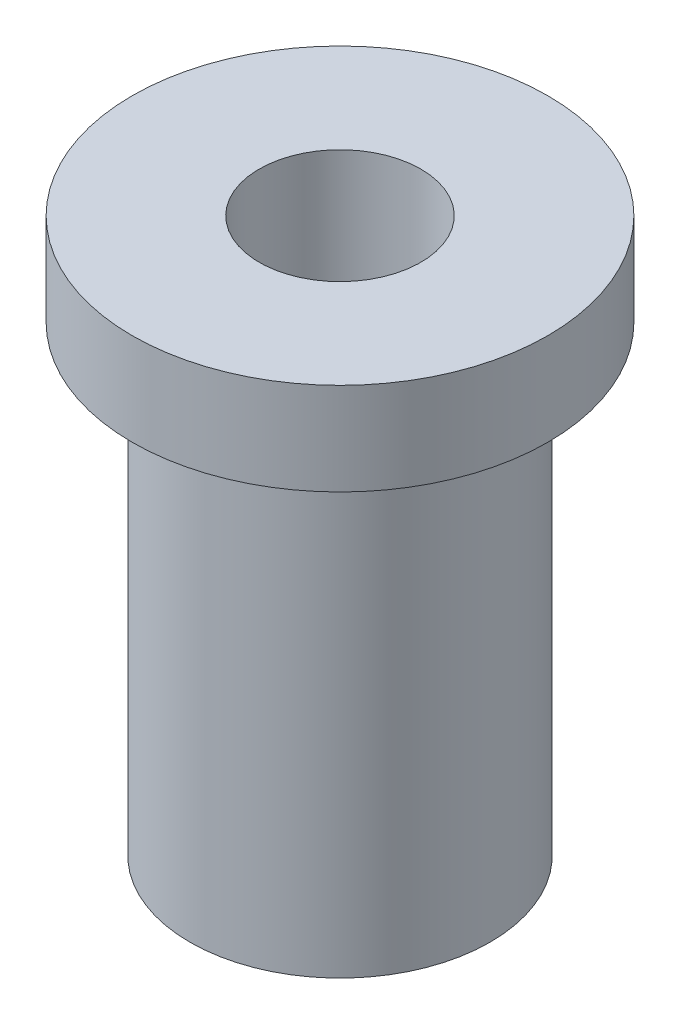
SolidWorks part; units mm, degrees
ref_plane "Front Plane" through (0, 0, 0) normal (0, 0, 1) x (1, 0, 0)
ref_plane "Top Plane" through (0, 0, 0) normal (0, 1, 0) x (1, 0, 0)
ref_plane "Right Plane" through (0, 0, 0) normal (1, 0, 0) x (0, 0, -1)
sketch "Sketch1" plane through (0, 0, 0) normal (0, 1, 0) x (1, 0, 0)
  circle A0 centre (0, 0) radius 4.5
extrude "Boss-Extrude1" add sketch "Sketch1" along normal blind 12
sketch "Sketch3" plane through (0, 0, 0) normal (0, -1, 0) x (-1, 0, 0)
  circle A0 centre (0, 0) radius 4.5
  circle A1 centre (0, 0) radius 3.25
extrude "Cut-Extrude1" cut sketch "Sketch3" against normal blind 10
sketch "Sketch4" plane through (0, 0, 0) normal (0, -1, 0) x (-1, 0, 0)
  circle A0 centre (0, 0) radius 1.75
extrude "Cut-Extrude2" cut sketch "Sketch4" against normal blind 12
